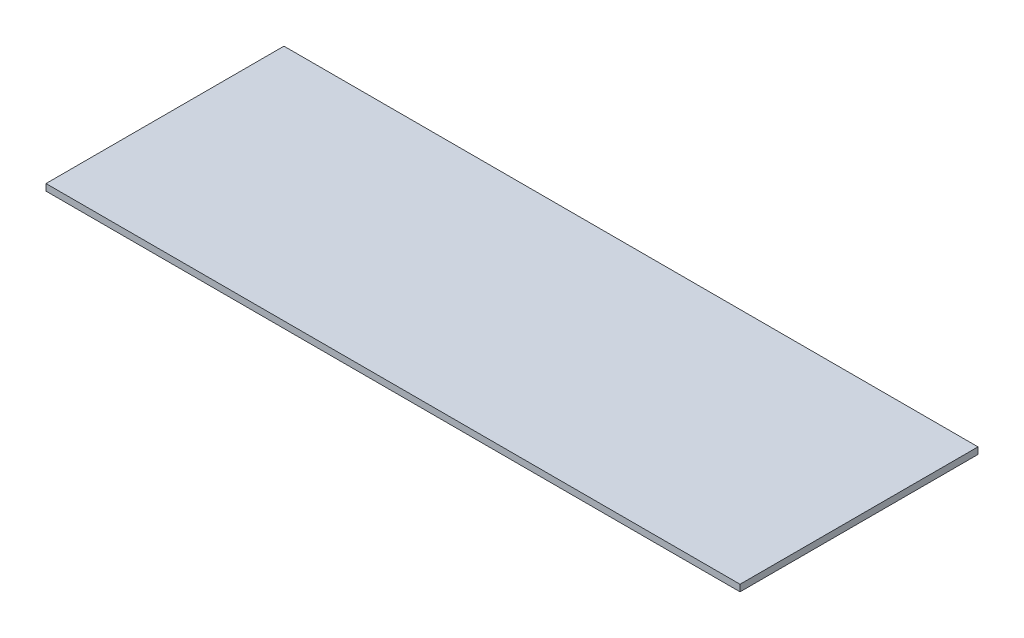
SolidWorks part; units mm, degrees
ref_plane "Front Plane" through (0, 0, 0) normal (0, 0, 1) x (1, 0, 0)
ref_plane "Top Plane" through (0, 0, 0) normal (0, 1, 0) x (1, 0, 0)
ref_plane "Right Plane" through (0, 0, 0) normal (1, 0, 0) x (0, 0, -1)
sketch "Sketch1" plane through (0, 0, 0) normal (0, 1, 0) x (1, 0, 0)
  line L1 (-105, -36) -> (105, -36)
  line L2 (-105, -36) -> (-105, 36)
  line L3 (-105, 36) -> (105, 36)
  line L4 (105, -36) -> (105, 36)
  line L5 (-105, -36) -> (105, 36) construction
  line L6 (-105, 36) -> (105, -36) construction
  point P0 (0, 0)
  dimension "D1" = 210
  dimension "D2" = 72
extrude "Boss-Extrude1" add sketch "Sketch1" along normal mid plane 2
